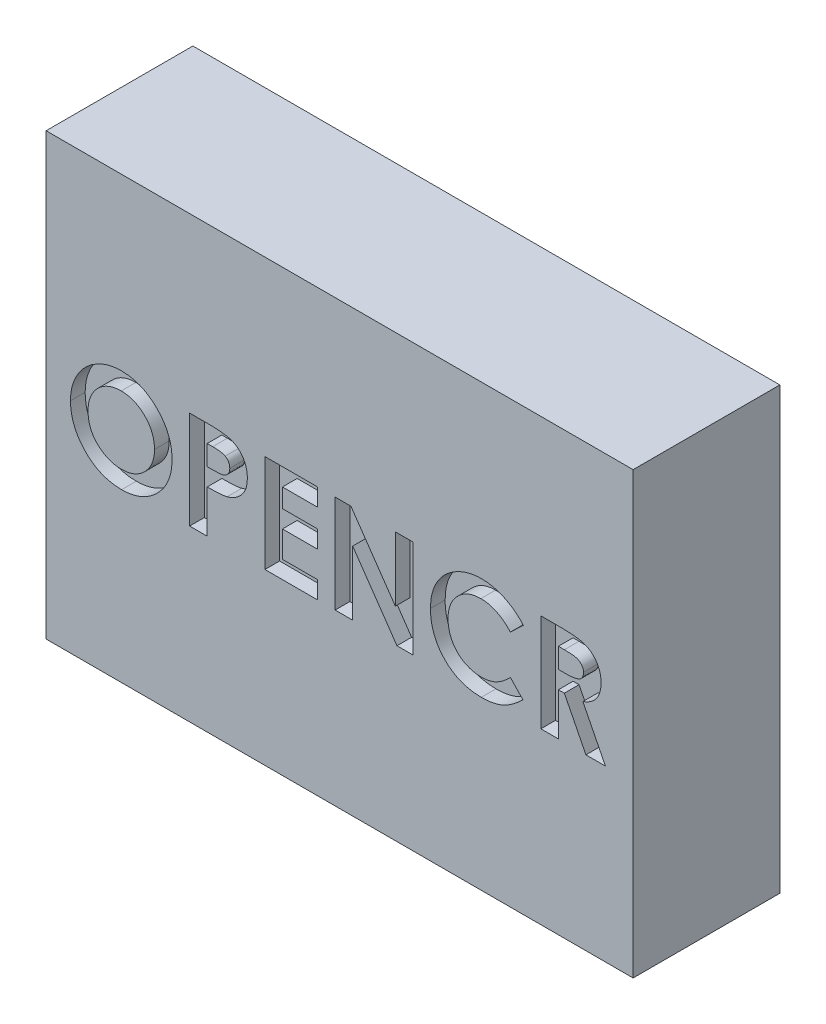
SolidWorks part; units mm, degrees
ref_plane "正面" through (0, 0, 0) normal (0, 0, 1) x (1, 0, 0)
ref_plane "平面" through (0, 0, 0) normal (0, 1, 0) x (1, 0, 0)
ref_plane "右側面" through (0, 0, 0) normal (1, 0, 0) x (0, 0, -1)
sketch "ｽｹｯﾁ1" plane through (0, 0, 0) normal (0, 0, 1) x (1, 0, 0)
  line L1 (0, 0) -> (120, 0)
  line L2 (0, 0) -> (0, 90)
  line L3 (0, 90) -> (120, 90)
  line L4 (120, 0) -> (120, 90)
  dimension "D1" = 90
  dimension "D2" = 120
extrude "ﾎﾞｽ - 押し出し1" add sketch "ｽｹｯﾁ1" along normal blind 30
sketch "ｽｹｯﾁ2" plane through (0, 0, 30) normal (0, 0, 1) x (1, 0, 0)
  text T0 "<b>OPENCR</b>" font "Century Gothic" height 20
extrude "ｶｯﾄ - 押し出し1" cut sketch "ｽｹｯﾁ2" against normal blind 3
